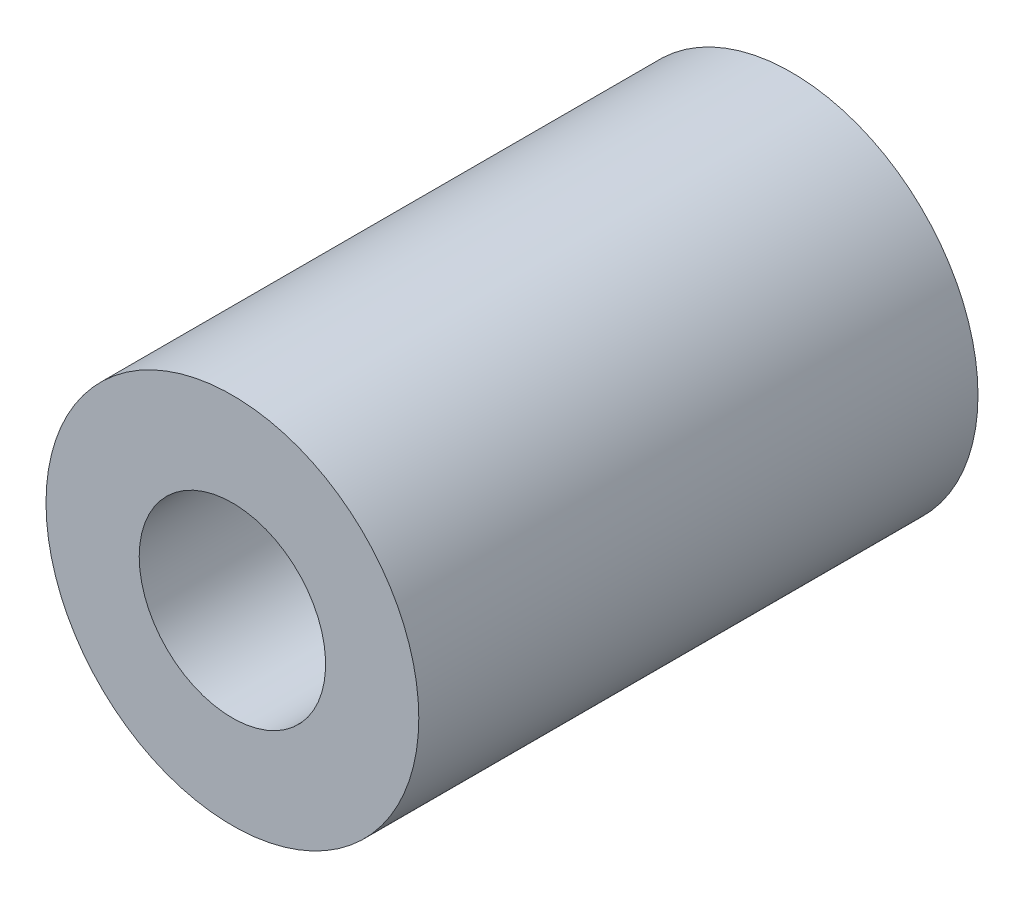
SolidWorks part; units mm, degrees
ref_plane "Front Plane" through (0, 0, 0) normal (0, 0, 1) x (1, 0, 0)
ref_plane "Top Plane" through (0, 0, 0) normal (0, 1, 0) x (1, 0, 0)
ref_plane "Right Plane" through (0, 0, 0) normal (1, 0, 0) x (0, 0, -1)
sketch "Sketch1" plane through (0, 0, 0) normal (0, 0, 1) x (1, 0, 0)
  circle A0 centre (-20.6394, 21.5957) radius 12.7
  circle A1 centre (-20.6394, 21.5957) radius 6.35
extrude "Boss-Extrude1" add sketch "Sketch1" along normal blind 38.1
